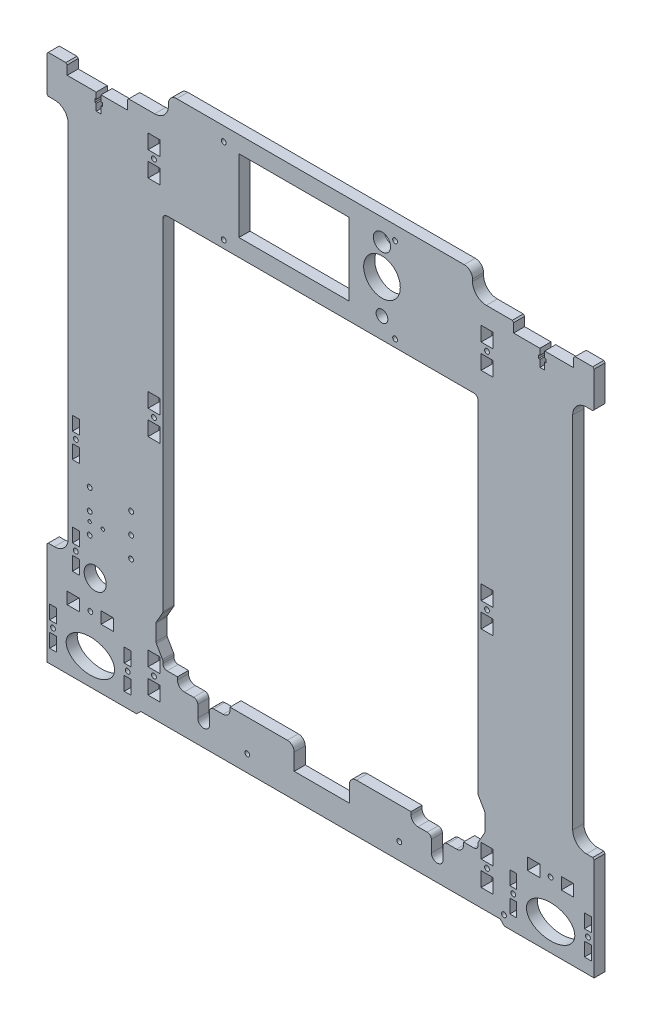
SolidWorks part; units mm, degrees
ref_plane "Front Plane" through (0, 0, 0) normal (0, 0, 1) x (1, 0, 0)
ref_plane "Top Plane" through (0, 0, 0) normal (0, 1, 0) x (1, 0, 0)
ref_plane "Right Plane" through (0, 0, 0) normal (1, 0, 0) x (0, 0, -1)
sketch "Sketch1" plane through (0, 0, 0) normal (0, 0, 1) x (1, 0, 0)
  line L0 (73.1283, 44.1292) -> (81.6283, 44.1292)
  line L1 (81.6283, 44.1292) -> (81.6283, 33.6292)
  line L2 (81.6283, 33.6292) -> (73.1283, 33.6292)
  line L3 (73.1283, 33.6292) -> (73.1283, 44.1292)
  line L4 (73.1283, 26.3792) -> (81.6283, 26.3792)
  line L5 (81.6283, 26.3792) -> (81.6283, 15.8792)
  line L6 (81.6283, 15.8792) -> (73.1283, 15.8792)
  line L7 (73.1283, 15.8792) -> (73.1283, 26.3792)
  line L8 (73.1283, 206.1292) -> (81.6283, 206.1292)
  line L9 (81.6283, 206.1292) -> (81.6283, 195.6292)
  line L10 (81.6283, 195.6292) -> (73.1283, 195.6292)
  line L11 (73.1283, 195.6292) -> (73.1283, 206.1292)
  line L12 (73.1283, 188.3792) -> (81.6283, 188.3792)
  line L13 (81.6283, 188.3792) -> (81.6283, 177.8792)
  line L14 (81.6283, 177.8792) -> (73.1283, 177.8792)
  line L15 (73.1283, 177.8792) -> (73.1283, 188.3792)
  line L16 (73.1283, 368.1292) -> (81.6283, 368.1292)
  line L17 (81.6283, 368.1292) -> (81.6283, 357.6292)
  line L18 (81.6283, 357.6292) -> (73.1283, 357.6292)
  line L19 (73.1283, 357.6292) -> (73.1283, 368.1292)
  line L20 (73.1283, 350.3792) -> (81.6283, 350.3792)
  line L21 (81.6283, 350.3792) -> (81.6283, 339.8792)
  line L22 (81.6283, 339.8792) -> (73.1283, 339.8792)
  line L23 (73.1283, 339.8792) -> (73.1283, 350.3792)
  line L24 (55.8783, 37.3792) -> (60.8783, 37.3792)
  line L25 (60.8783, 37.3792) -> (60.8783, 27.3792)
  line L26 (60.8783, 27.3792) -> (55.8783, 27.3792)
  line L27 (55.8783, 27.3792) -> (55.8783, 37.3792)
  line L28 (55.8783, 19.6292) -> (60.8783, 19.6292)
  line L29 (60.8783, 19.6292) -> (60.8783, 9.6292)
  line L30 (60.8783, 9.6292) -> (55.8783, 9.6292)
  line L31 (55.8783, 9.6292) -> (55.8783, 19.6292)
  line L32 (6.8783, 37.3792) -> (1.8783, 37.3792)
  line L33 (1.8783, 37.3792) -> (1.8783, 27.3792)
  line L34 (1.8783, 27.3792) -> (6.8783, 27.3792)
  line L35 (6.8783, 27.3792) -> (6.8783, 37.3792)
  line L36 (6.8783, 19.6292) -> (1.8783, 19.6292)
  line L37 (1.8783, 19.6292) -> (1.8783, 9.6292)
  line L38 (1.8783, 9.6292) -> (6.8783, 9.6292)
  line L39 (6.8783, 9.6292) -> (6.8783, 19.6292)
  line L40 (39.1283, 51.7542) -> (48.1283, 51.7542)
  line L41 (48.1283, 51.7542) -> (48.1283, 43.2542)
  line L42 (48.1283, 43.2542) -> (39.1283, 43.2542)
  line L43 (39.1283, 43.2542) -> (39.1283, 51.7542)
  line L44 (23.6283, 51.7542) -> (14.6283, 51.7542)
  line L45 (14.6283, 51.7542) -> (14.6283, 43.2542)
  line L46 (14.6283, 43.2542) -> (23.6283, 43.2542)
  line L47 (23.6283, 43.2542) -> (23.6283, 51.7542)
  line L48 (39.1283, 375.0042) -> (58.1283, 375.0042)
  line L49 (18.3783, 93.8792) -> (23.3783, 93.8792)
  line L50 (23.3783, 93.8792) -> (23.3783, 83.8792)
  line L51 (23.3783, 83.8792) -> (18.3783, 83.8792)
  line L52 (18.3783, 83.8792) -> (18.3783, 93.8792)
  line L53 (18.3783, 76.1292) -> (23.3783, 76.1292)
  line L54 (23.3783, 76.1292) -> (23.3783, 66.1292)
  line L55 (23.3783, 66.1292) -> (18.3783, 66.1292)
  line L56 (18.3783, 66.1292) -> (18.3783, 76.1292)
  line L57 (18.3783, 163.8792) -> (23.3783, 163.8792)
  line L58 (23.3783, 163.8792) -> (23.3783, 153.8792)
  line L59 (23.3783, 153.8792) -> (18.3783, 153.8792)
  line L60 (18.3783, 153.8792) -> (18.3783, 163.8792)
  line L61 (18.3783, 146.1292) -> (23.3783, 146.1292)
  line L62 (23.3783, 146.1292) -> (23.3783, 136.1292)
  line L63 (23.3783, 136.1292) -> (18.3783, 136.1292)
  line L64 (18.3783, 136.1292) -> (18.3783, 146.1292)
  line L65 (322.6283, 44.1292) -> (314.1283, 44.1292)
  line L66 (314.1283, 44.1292) -> (314.1283, 33.6292)
  line L67 (314.1283, 33.6292) -> (322.6283, 33.6292)
  line L68 (322.6283, 33.6292) -> (322.6283, 44.1292)
  line L69 (322.6283, 26.3792) -> (314.1283, 26.3792)
  line L70 (314.1283, 26.3792) -> (314.1283, 15.8792)
  line L71 (314.1283, 15.8792) -> (322.6283, 15.8792)
  line L72 (322.6283, 15.8792) -> (322.6283, 26.3792)
  line L73 (322.6283, 206.1292) -> (314.1283, 206.1292)
  line L74 (314.1283, 206.1292) -> (314.1283, 195.6292)
  line L75 (314.1283, 195.6292) -> (322.6283, 195.6292)
  line L76 (322.6283, 195.6292) -> (322.6283, 206.1292)
  line L77 (322.6283, 188.3792) -> (314.1283, 188.3792)
  line L78 (314.1283, 188.3792) -> (314.1283, 177.8792)
  line L79 (314.1283, 177.8792) -> (322.6283, 177.8792)
  line L80 (322.6283, 177.8792) -> (322.6283, 188.3792)
  line L81 (322.6283, 368.1292) -> (314.1283, 368.1292)
  line L82 (314.1283, 368.1292) -> (314.1283, 357.6292)
  line L83 (314.1283, 357.6292) -> (322.6283, 357.6292)
  line L84 (322.6283, 357.6292) -> (322.6283, 368.1292)
  line L85 (322.6283, 350.3792) -> (314.1283, 350.3792)
  line L86 (314.1283, 350.3792) -> (314.1283, 339.8792)
  line L87 (314.1283, 339.8792) -> (322.6283, 339.8792)
  line L88 (322.6283, 339.8792) -> (322.6283, 350.3792)
  line L89 (339.8783, 37.3792) -> (334.8783, 37.3792)
  line L90 (334.8783, 37.3792) -> (334.8783, 27.3792)
  line L91 (334.8783, 27.3792) -> (339.8783, 27.3792)
  line L92 (339.8783, 27.3792) -> (339.8783, 37.3792)
  line L93 (339.8783, 19.6292) -> (334.8783, 19.6292)
  line L94 (334.8783, 19.6292) -> (334.8783, 9.6292)
  line L95 (334.8783, 9.6292) -> (339.8783, 9.6292)
  line L96 (339.8783, 9.6292) -> (339.8783, 19.6292)
  line L97 (388.8783, 37.3792) -> (393.8783, 37.3792)
  line L98 (393.8783, 37.3792) -> (393.8783, 27.3792)
  line L99 (393.8783, 27.3792) -> (388.8783, 27.3792)
  line L100 (388.8783, 27.3792) -> (388.8783, 37.3792)
  line L101 (388.8783, 19.6292) -> (393.8783, 19.6292)
  line L102 (393.8783, 19.6292) -> (393.8783, 9.6292)
  line L103 (393.8783, 9.6292) -> (388.8783, 9.6292)
  line L104 (388.8783, 9.6292) -> (388.8783, 19.6292)
  line L105 (356.6283, 51.7542) -> (347.6283, 51.7542)
  line L106 (347.6283, 51.7542) -> (347.6283, 43.2542)
  line L107 (347.6283, 43.2542) -> (356.6283, 43.2542)
  line L108 (356.6283, 43.2542) -> (356.6283, 51.7542)
  line L109 (372.1283, 51.7542) -> (381.1283, 51.7542)
  line L110 (381.1283, 51.7542) -> (381.1283, 43.2542)
  line L111 (381.1283, 43.2542) -> (372.1283, 43.2542)
  line L112 (372.1283, 43.2542) -> (372.1283, 51.7542)
  line L113 (356.6283, 375.0042) -> (337.6283, 375.0042)
  line L114 (218.8783, 38.0042) -> (218.8783, 21.0042)
  line L115 (218.8783, 21.0042) -> (178.8783, 21.0042)
  line L116 (178.8783, 21.0042) -> (178.8783, 38.0042)
  line L117 (178.8783, 38.0042) -> (132.3783, 38.0042)
  line L118 (132.3783, 38.0042) -> (132.3783, 36.0042)
  line L119 (127.3783, 31.0042) -> (117.6283, 31.0042)
  line L120 (117.6283, 31.0042) -> (117.6283, 19.5042)
  line L121 (109.1283, 19.5042) -> (109.1283, 31.0042)
  line L122 (109.1283, 31.0042) -> (99.3783, 31.0042)
  line L123 (94.3783, 36.0042) -> (94.3783, 38.0042)
  line L124 (94.3783, 38.0042) -> (86.8783, 38.0042)
  line L125 (83.8783, 41.0042) -> (83.8783, 320.0042)
  line L126 (86.8783, 323.0042) -> (308.8783, 323.0042)
  line L127 (311.8783, 320.0042) -> (311.8783, 41.0042)
  line L128 (308.8783, 38.0042) -> (301.3783, 38.0042)
  line L129 (301.3783, 38.0042) -> (301.3783, 36.0042)
  line L130 (296.3783, 31.0042) -> (286.6283, 31.0042)
  line L131 (286.6283, 31.0042) -> (286.6283, 19.5042)
  line L132 (278.1283, 19.5042) -> (278.1283, 31.0042)
  line L133 (278.1283, 31.0042) -> (268.3783, 31.0042)
  line L134 (263.3783, 36.0042) -> (263.3783, 38.0042)
  line L135 (263.3783, 38.0042) -> (218.8783, 38.0042)
  line L136 (138.8783, 388.0042) -> (218.3783, 388.0042)
  line L137 (218.3783, 388.0042) -> (218.3783, 335.5042)
  line L138 (218.3783, 335.5042) -> (138.8783, 335.5042)
  line L139 (138.8783, 335.5042) -> (138.8783, 388.0042)
  line L140 (35.6283, 375.0042) -> (14.6283, 375.0042)
  line L141 (14.6283, 375.0042) -> (14.6283, 381.5042)
  line L142 (14.6283, 381.5042) -> (13.6283, 382.5042)
  line L143 (13.6283, 382.5042) -> (0.8783, 382.5042)
  line L144 (0.8783, 382.5042) -> (-0.1217, 381.5042)
  line L145 (-0.1217, 381.5042) -> (-0.1217, 356.0042)
  line L146 (-0.1217, 356.0042) -> (0.8783, 355.0042)
  line L147 (0.8783, 355.0042) -> (5.3783, 355.0042)
  line L148 (15.3783, 345.0042) -> (15.3783, 85.0042)
  line L149 (5.3783, 75.0042) -> (0.8783, 75.0042)
  line L150 (0.8783, 75.0042) -> (-0.1217, 74.0042)
  line L151 (-0.1217, 74.0042) -> (-0.1217, 0.0042)
  line L152 (-0.1217, 0.0042) -> (64.8783, 0.0042)
  line L153 (64.8783, 0.0042) -> (67.8783, 3.0042)
  line L154 (67.8783, 3.0042) -> (327.8783, 3.0042)
  line L155 (327.8783, 3.0042) -> (330.8783, 0.0042)
  line L156 (330.8783, 0.0042) -> (395.8783, 0.0042)
  line L157 (395.8783, 0.0042) -> (395.8783, 74.0042)
  line L158 (395.8783, 74.0042) -> (394.8783, 75.0042)
  line L159 (394.8783, 75.0042) -> (390.3783, 75.0042)
  line L160 (380.3783, 85.0042) -> (380.3783, 345.0042)
  line L161 (390.3783, 355.0042) -> (394.8783, 355.0042)
  line L162 (394.8783, 355.0042) -> (395.8783, 356.0042)
  line L163 (395.8783, 356.0042) -> (395.8783, 381.5042)
  line L164 (395.8783, 381.5042) -> (394.8783, 382.5042)
  line L165 (394.8783, 382.5042) -> (382.1283, 382.5042)
  line L166 (382.1283, 382.5042) -> (381.1283, 381.5042)
  line L167 (381.1283, 381.5042) -> (381.1283, 375.0042)
  line L168 (381.1283, 375.0042) -> (360.1283, 375.0042)
  line L169 (360.1283, 375.0042) -> (360.1283, 370.5042)
  line L170 (360.1283, 370.5042) -> (361.1283, 370.5042)
  line L171 (361.1283, 370.5042) -> (361.1283, 368.0042)
  line L172 (361.1283, 368.0042) -> (360.1283, 368.0042)
  line L173 (360.1283, 368.0042) -> (360.1283, 363.0042)
  line L174 (360.1283, 363.0042) -> (356.6283, 363.0042)
  line L175 (356.6283, 363.0042) -> (356.6283, 368.0042)
  line L176 (356.6283, 368.0042) -> (355.6283, 368.0042)
  line L177 (355.6283, 368.0042) -> (355.6283, 370.5042)
  line L178 (355.6283, 370.5042) -> (356.6283, 370.5042)
  line L179 (356.6283, 370.5042) -> (356.6283, 375.0042)
  line L181 (337.6283, 375.0042) -> (337.6283, 381.5042)
  line L182 (337.6283, 381.5042) -> (336.6283, 382.5042)
  line L183 (336.6283, 382.5042) -> (317.8783, 382.5042)
  line L184 (307.8783, 392.5042) -> (307.8783, 394.0042)
  line L185 (301.8783, 400.0042) -> (93.8783, 400.0042)
  line L186 (87.8783, 394.0042) -> (87.8783, 392.5042)
  line L187 (77.8783, 382.5042) -> (59.1283, 382.5042)
  line L188 (59.1283, 382.5042) -> (58.1283, 381.5042)
  line L189 (58.1283, 381.5042) -> (58.1283, 375.0042)
  line L191 (39.1283, 375.0042) -> (39.1283, 370.5042)
  line L192 (39.1283, 370.5042) -> (40.1283, 370.5042)
  line L193 (40.1283, 370.5042) -> (40.1283, 368.0042)
  line L194 (40.1283, 368.0042) -> (39.1283, 368.0042)
  line L195 (39.1283, 368.0042) -> (39.1283, 363.0042)
  line L196 (39.1283, 363.0042) -> (35.6283, 363.0042)
  line L197 (35.6283, 363.0042) -> (35.6283, 368.0042)
  line L198 (35.6283, 368.0042) -> (34.6283, 368.0042)
  line L199 (34.6283, 368.0042) -> (34.6283, 370.5042)
  line L200 (34.6283, 370.5042) -> (35.6283, 370.5042)
  line L201 (35.6283, 370.5042) -> (35.6283, 375.0042)
  circle A0 centre (77.3783, 30.0042) radius 1.75
  circle A1 centre (77.3783, 192.0042) radius 1.75
  circle A2 centre (77.3783, 354.0042) radius 1.75
  circle A3 centre (58.3783, 23.5042) radius 1.75
  circle A4 centre (4.3783, 23.5042) radius 1.75
  circle A5 centre (31.3783, 47.5042) radius 1.75
  circle A6 centre (20.8783, 80.0042) radius 1.75
  circle A7 centre (20.8783, 150.0042) radius 1.75
  circle A8 centre (34.8783, 70.0042) radius 8
  circle A9 centre (318.3783, 30.0042) radius 1.75
  circle A10 centre (318.3783, 192.0042) radius 1.75
  circle A11 centre (318.3783, 354.0042) radius 1.75
  circle A12 centre (337.3783, 23.5042) radius 1.75
  circle A13 centre (391.3783, 23.5042) radius 1.75
  circle A14 centre (364.3783, 47.5042) radius 1.75
  circle A15 centre (30.8783, 103.5042) radius 1.2
  circle A16 centre (40.3783, 103.5042) radius 1.2
  circle A17 centre (251.8783, 328.5042) radius 1.75
  circle A18 centre (127.8783, 328.5042) radius 1.75
  circle A19 centre (251.8783, 390.0042) radius 1.75
  circle A20 centre (127.8783, 390.0042) radius 1.75
  arc A21 (127.3783, 31.0042) -> (132.3783, 36.0042) centre (127.3783, 36.0042) ccw
  arc A22 (109.1283, 19.5042) -> (117.6283, 19.5042) centre (113.3783, 19.5042) ccw
  arc A23 (94.3783, 36.0042) -> (99.3783, 31.0042) centre (99.3783, 36.0042) ccw
  arc A24 (83.8783, 41.0042) -> (86.8783, 38.0042) centre (86.8783, 41.0042) ccw
  arc A25 (86.8783, 323.0042) -> (83.8783, 320.0042) centre (86.8783, 320.0042) ccw
  arc A26 (311.8783, 320.0042) -> (308.8783, 323.0042) centre (308.8783, 320.0042) ccw
  arc A27 (308.8783, 38.0042) -> (311.8783, 41.0042) centre (308.8783, 41.0042) ccw
  arc A28 (296.3783, 31.0042) -> (301.3783, 36.0042) centre (296.3783, 36.0042) ccw
  arc A29 (278.1283, 19.5042) -> (286.6283, 19.5042) centre (282.3783, 19.5042) ccw
  arc A30 (263.3783, 36.0042) -> (268.3783, 31.0042) centre (268.3783, 36.0042) ccw
  circle A31 centre (242.3783, 362.5042) radius 13.25
  circle A32 centre (242.3783, 384.5042) radius 6.25
  circle A33 centre (242.3783, 338.0042) radius 4.25
  circle A34 centre (144.8783, 15.0042) radius 1.75
  circle A35 centre (254.8783, 15.0042) radius 1.75
  arc A36 (15.3783, 345.0042) -> (5.3783, 355.0042) centre (5.3783, 345.0042) ccw
  arc A37 (5.3783, 75.0042) -> (15.3783, 85.0042) centre (5.3783, 85.0042) ccw
  arc A38 (380.3783, 85.0042) -> (390.3783, 75.0042) centre (390.3783, 85.0042) ccw
  arc A39 (390.3783, 355.0042) -> (380.3783, 345.0042) centre (390.3783, 345.0042) ccw
  arc A40 (307.8783, 392.5042) -> (317.8783, 382.5042) centre (317.8783, 392.5042) ccw
  arc A41 (307.8783, 394.0042) -> (301.8783, 400.0042) centre (301.8783, 394.0042) ccw
  arc A42 (93.8783, 400.0042) -> (87.8783, 394.0042) centre (93.8783, 394.0042) ccw
  arc A43 (77.8783, 382.5042) -> (87.8783, 392.5042) centre (77.8783, 392.5042) ccw
  ellipse E0 centre (31.3783, 19.5042) end of major axis (13.8783, 19.5042) minor radius 12
  ellipse E1 centre (364.3783, 19.5042) end of major axis (381.8783, 19.5042) minor radius 12
extrude "Extrude1" add sketch "Sketch1" along normal blind 8
sketch "Sketch2" plane through (0, 363.0042, 0) normal (0, 1, 0) x (1, 0, 0)
  line L0 (360.1283, 0) -> (356.6283, -8)
  circle A0 centre (358.3783, -4) radius 1
  point P4 (358.3783, -4)
extrude "Extrude2" cut sketch "Sketch2" against normal blind 1 contours A0
sketch "Sketch3" plane through (0, 363.0042, 0) normal (0, 1, 0) x (1, 0, 0)
  line L0 (35.6283, 0) -> (39.1283, -8)
  circle A0 centre (37.3783, -4) radius 1
extrude "Extrude3" cut sketch "Sketch3" against normal blind 1 contours A0
sketch "Sketch4" plane through (0, 0, 8) normal (0, 0, 1) x (1, 0, 0)
  line L0 (311.8783, 43.0042) -> (316.8783, 51.6645)
  line L1 (311.8783, 41.0042) -> (311.8783, 320.0042) construction
  line L2 (316.8783, 51.6645) -> (316.8783, 64.344)
  line L3 (316.8783, 64.344) -> (311.8783, 73.0042)
  line L4 (311.8783, 73.0042) -> (311.8783, 43.0042)
  line L5 (67.8783, 3.0042) -> (327.8783, 3.0042) construction
  line L6 (83.8783, 43.0042) -> (83.8783, 73.0042)
  line L7 (83.8783, 320.0042) -> (83.8783, 41.0042) construction
  line L8 (83.8783, 73.0042) -> (78.8783, 64.344)
  line L9 (78.8783, 64.344) -> (78.8783, 51.6645)
  line L10 (78.8783, 51.6645) -> (83.8783, 43.0042)
  dimension "D1" = 40
  dimension "D2" = 30
  dimension "D3" = 30
  dimension "D4" = 30
  dimension "D5" = 5
  dimension "D6" = 40
  dimension "D7" = 30
  dimension "D8" = 30
  dimension "D9" = 5
  dimension "D10" = 30
extrude "Cut-Extrude1" cut sketch "Sketch4" against normal through all
fillet "Fillet1" radius 2 8 edges at (311.8783, 73.0042, 4) (316.8783, 64.344, 4) (316.8783, 51.6645, 4) (311.8783, 43.0042, 4) (83.8783, 73.0042, 4) (78.8783, 64.344, 4) (78.8783, 51.6645, 4) (83.8783, 43.0042, 4)
fillet "Fillet2" radius 5 2 edges at (218.8783, 38.0042, 4) (178.8783, 38.0042, 4)
fillet "Fillet3" radius 3 4 edges at (286.6283, 31.0042, 4) (278.1283, 31.0042, 4) (117.6283, 31.0042, 4) (109.1283, 31.0042, 4)
sketch "Sketch5" plane through (0, 0, 8) normal (0, 0, 1) x (1, 0, 0)
  line L0 (318.3783, 15.8792) -> (318.3783, 7.0042) construction
  line L1 (314.1283, 15.8792) -> (322.6283, 15.8792) construction
  line L2 (318.3783, 7.0042) -> (330.6283, 7.0042) construction
  line L3 (330.8783, 0.0042) -> (395.8783, 0.0042) construction
  circle A1 centre (330.6283, 7.0042) radius 1.75
  dimension "D3" = 3.5
  dimension "D1" = 7
  dimension "D2" = 12.25
extrude "Cut-Extrude2" cut sketch "Sketch5" against normal through all
sketch "Sketch6" plane through (0, 0, 8) normal (0, 0, 1) x (1, 0, 0)
  line L0 (-0.1217, 55.0042) -> (45.8783, 55.0042) construction
  line L2 (-0.1217, 74.0042) -> (-0.1217, 0.0042) construction
  line L3 (-0.1217, 0.0042) -> (64.8783, 0.0042) construction
  line L4 (83.8783, 320.0042) -> (83.8783, 73.5401) construction
  line L5 (45.8783, 55.0042) -> (45.8783, 95.0042) construction
  line L6 (45.8783, 95.0042) -> (30.8783, 95.0042) construction
  line L7 (30.8783, 95.0042) -> (60.8783, 95.0042) construction
  circle A0 centre (30.8783, 95.0042) radius 1.75
  circle A1 centre (60.8783, 95.0042) radius 1.75
  circle A2 centre (60.8783, 110.0042) radius 1.75
  circle A3 centre (30.8783, 110.0042) radius 1.75
  circle A4 centre (60.8783, 125.0042) radius 1.75
  circle A5 centre (30.8783, 125.0042) radius 1.75
  dimension "D6" = 3.5
  dimension "D7" = 3.5
  dimension "D8" = 15
  dimension "D9" = 15
  dimension "D10" = 30
  dimension "D11" = 15
  dimension "D12" = 3.5
  dimension "D13" = 15
  dimension "D14" = 15
  dimension "D15" = 3.5
  dimension "D16" = 3.5
  dimension "D17" = 3.5
  dimension "D19" = 15
  dimension "D1" = 55
  dimension "D2" = 38
  dimension "D3" = 40
  dimension "D4" = 15
  dimension "D5" = 30
  dimension "D18" = 15
extrude "Cut-Extrude3" cut sketch "Sketch6" against normal through all
